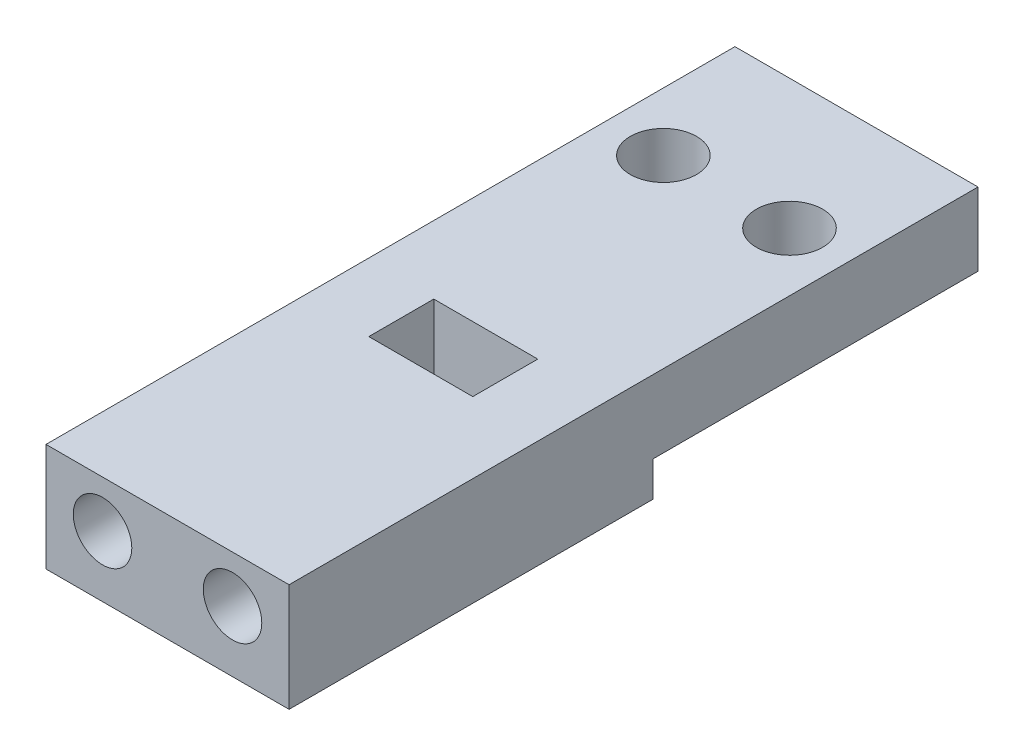
SolidWorks part; units mm, degrees
ref_plane "前视基准面" through (0, 0, 0) normal (0, 0, 1) x (1, 0, 0)
ref_plane "上视基准面" through (0, 0, 0) normal (0, 1, 0) x (1, 0, 0)
ref_plane "右视基准面" through (0, 0, 0) normal (1, 0, 0) x (0, 0, -1)
other "Configuration Table"
sketch "草图1" plane through (0, 0, 0) normal (0, 0, 1) x (1, 0, 0)
  line L1 (-11.1667, -5) -> (11.1667, -5)
  line L2 (-11.1667, -5) -> (-11.1667, 5)
  line L3 (-11.1667, 5) -> (11.1667, 5)
  line L4 (11.1667, -5) -> (11.1667, 5)
  line L5 (-11.1667, -5) -> (11.1667, 5) construction
  line L6 (-11.1667, 5) -> (11.1667, -5) construction
  point P0 (0, 0)
  dimension "D1" = 10
extrude "凸台-拉伸1" add sketch "草图1" along normal blind 30
sketch "草图2" plane through (0, -5, 0) normal (0, -1, 0) x (1, 0, 0)
  line L0 (-10.0833, 30.4566) -> (-10.0833, 0)
  line L1 (-10.0833, 30) -> (-10.0833, 38.1808) construction
  line L2 (-11.1667, 0) -> (11.1667, 0) construction
sketch "草图3" plane through (0, 0, 30) normal (0, 0, 1) x (1, 0, 0)
  line L0 (-9.2333, 0.05) -> (-9.2333, -5.0113)
  line L2 (9.4667, -5) -> (9.4667, 0.05)
  circle A0 centre (5.1167, -0.3) radius 2.25
  circle A1 centre (-4.8833, -0.3) radius 2.25
  arc A3 (9.4667, 0.05) -> (7.4667, 2.05) centre (7.4667, 0.05) ccw
  arc A4 (-9.2333, 0.05) -> (-6.4511, 1.8907) centre (-7.2333, 0.05) cw
sketch "草图4" plane through (0, -5, 0) normal (0, -1, 0) x (1, 0, 0)
  line L1 (-11.1667, 30) -> (-10.0833, 30)
  line L2 (-11.1667, 30) -> (-11.1667, 0)
  line L3 (-11.1667, 0) -> (-10.0833, 0)
  line L4 (-10.0833, 30) -> (-10.0833, 0)
extrude "切除-拉伸1" cut sketch "草图4" against normal blind 30
extrude "切除-拉伸2" cut sketch "草图3" against normal blind 15 contours A1 | A0
sketch "草图5" plane through (0, 0, 30) normal (0, 0, 1) x (1, 0, 0)
  line L0 (9.4667, -5) -> (9.4667, 0.05) construction
  line L1 (-9.2333, -5.0113) -> (9.4667, -5.0113)
  line L2 (-9.2333, -5.0113) -> (-9.2333, 3.3044)
  line L3 (-9.2333, 3.3044) -> (9.4667, 3.3044)
  line L4 (9.4667, -5.0113) -> (9.4667, 3.3044)
extrude "切除-拉伸3" cut sketch "草图5" against normal blind 30 flip side to cut
sketch "草图6" plane through (9.4667, 0, 0) normal (1, 0, 0) x (0, 0, -1)
  line L0 (22.3266, -2.313) -> (13.2059, -2.313) construction
sketch "草图7" plane through (0, 3.3044, 0) normal (0, 1, 0) x (1, 0, 0)
  arc A0 (-18.3547, 13) -> (-15.8066, 10.45) centre (-15.8066, 12.9981) cw
sketch "草图10" plane through (0, 0, 0) normal (0, 0, -1) x (-1, 0, 0)
  line L4 (-9.4667, -5) -> (9.2333, -5)
  line L5 (9.2333, -5) -> (9.2333, 3.3044)
  line L6 (9.2333, 3.3044) -> (-9.4667, 3.3044)
  line L7 (-9.4667, 3.3044) -> (-9.4667, -5)
  line L8 (-9.4667, -5) -> (9.2333, -5)
  line L9 (9.2333, -5) -> (9.2333, 3.3044)
  line L10 (9.2333, 3.3044) -> (-9.4667, 3.3044)
  line L11 (-9.4667, 3.3044) -> (-9.4667, -5)
  dimension "D1" = 0
extrude "凸台-拉伸2" add sketch "草图10" along normal blind 18
sketch "草图11" plane through (9.4667, 0, 0) normal (1, 0, 0) x (0, 0, -1)
  line L1 (18, -5) -> (-2, -5)
  line L2 (18, -5) -> (18, -2.313)
  line L3 (18, -2.313) -> (-2, -2.313)
  line L4 (-2, -5) -> (-2, -2.313)
  dimension "D1" = 20
extrude "切除-拉伸5" cut sketch "草图11" against normal through all
sketch "草图12" plane through (0, -2.313, 0) normal (0, -1, 0) x (1, 0, 0)
  line L0 (-9.2333, -12.9981) -> (9.4667, -12.9981)
  line L1 (-9.2333, -18) -> (-9.2333, 2) construction
  line L2 (9.4667, -200022.3266) -> (9.4667, 199986.7941) construction
  circle A0 centre (-4.7333, -12.9981) radius 2.5481
  circle A1 centre (4.9667, -12.9981) radius 2.5481
  point P5 (-4.7333, -12.9981)
  point P8 (4.9667, -12.9981)
  point P11 (0.1167, -12.9981)
  dimension "D1" = 4.5
  dimension "D2" = 4.5
extrude "切除-拉伸6" cut sketch "草图12" against normal through all contours L0 A0 | L0 A0 | L0 A1 | L0 A1
sketch "草图13" plane through (0, 3.3044, 0) normal (0, 1, 0) x (1, 0, 0)
  line L0 (-9.2333, 18) -> (-9.2333, -30) construction
  line L1 (9.4667, 18) -> (-9.2333, 18)
  line L2 (9.4667, 18) -> (9.4667, 23)
  line L3 (9.4667, 23) -> (-9.2333, 23)
  line L4 (-9.2333, 18) -> (-9.2333, 23)
extrude "凸台-拉伸3" add sketch "草图13" against normal up to surface (5.6174 mm away) up to face at (-4.7333, -2.313, -15.5463)
sketch "草图14" plane through (0, 3.3044, 0) normal (0, 1, 0) x (1, 0, 0)
  line L1 (-4, -5.4) -> (4, -5.4)
  line L2 (-4, -5.4) -> (-4, -10.4)
  line L3 (-4, -10.4) -> (4, -10.4)
  line L4 (4, -5.4) -> (4, -10.4)
  dimension "D1" = 4
  dimension "D2" = 4
  dimension "D3" = 5.4
  dimension "D4" = 5
extrude "切除-拉伸7" cut sketch "草图14" against normal through all
